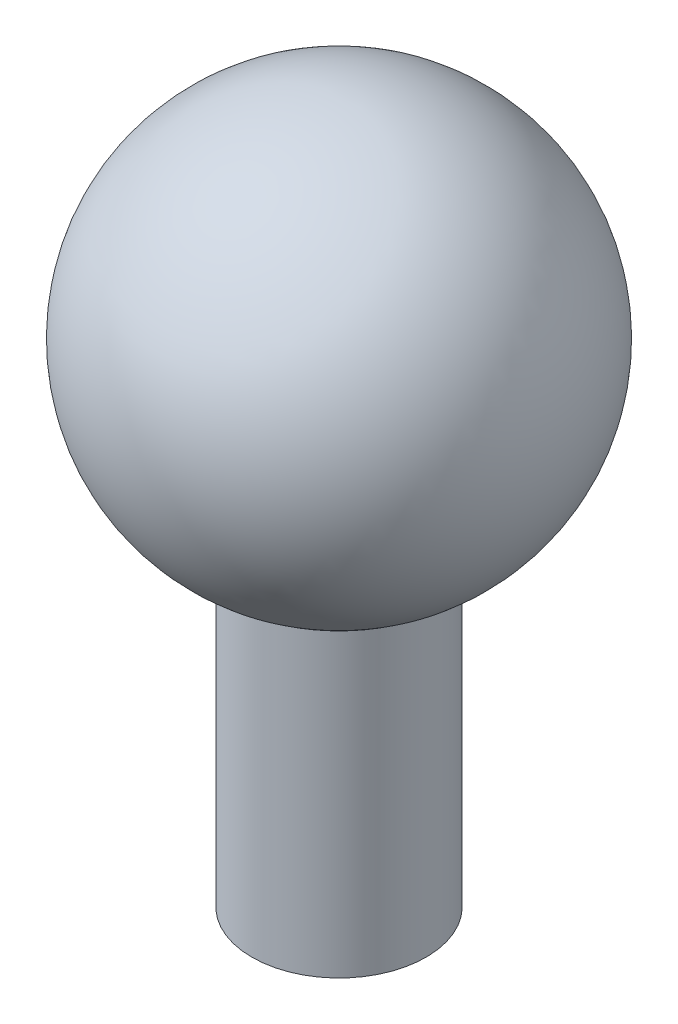
SolidWorks part; units mm, degrees
ref_plane "Front Plane" through (0, 0, 0) normal (0, 0, 1) x (1, 0, 0)
ref_plane "Top Plane" through (0, 0, 0) normal (0, 1, 0) x (1, 0, 0)
ref_plane "Right Plane" through (0, 0, 0) normal (1, 0, 0) x (0, 0, -1)
sketch "Sketch1" plane through (0, 0, 0) normal (0, 1, 0) x (1, 0, 0)
  circle A0 centre (0, 0) radius 1
  dimension "D1" = 2
extrude "Boss-Extrude1" add sketch "Sketch1" along normal blind 3.5 contours A0
sketch "Sketch2" plane through (0, 0, 0) normal (0, 0, 1) x (1, 0, 0)
  line L2 (0, 3.2766) -> (0, 8.0266)
  arc A2 (0, 8.0266) -> (0, 3.2766) centre (0, 5.6516) ccw
  dimension "D1" = 4.75
revolve "Revolve2" add sketch "Sketch2" angle 360 about L2
ref_plane "Plane1" through (0, 3.4974, 0) normal (0, -1, 0) x (-1, 0, 0)
sketch "Sketch3" plane through (0, 3.4974, 0) normal (0, -1, 0) x (-1, 0, 0)
  circle A0 centre (0, 0) radius 1
